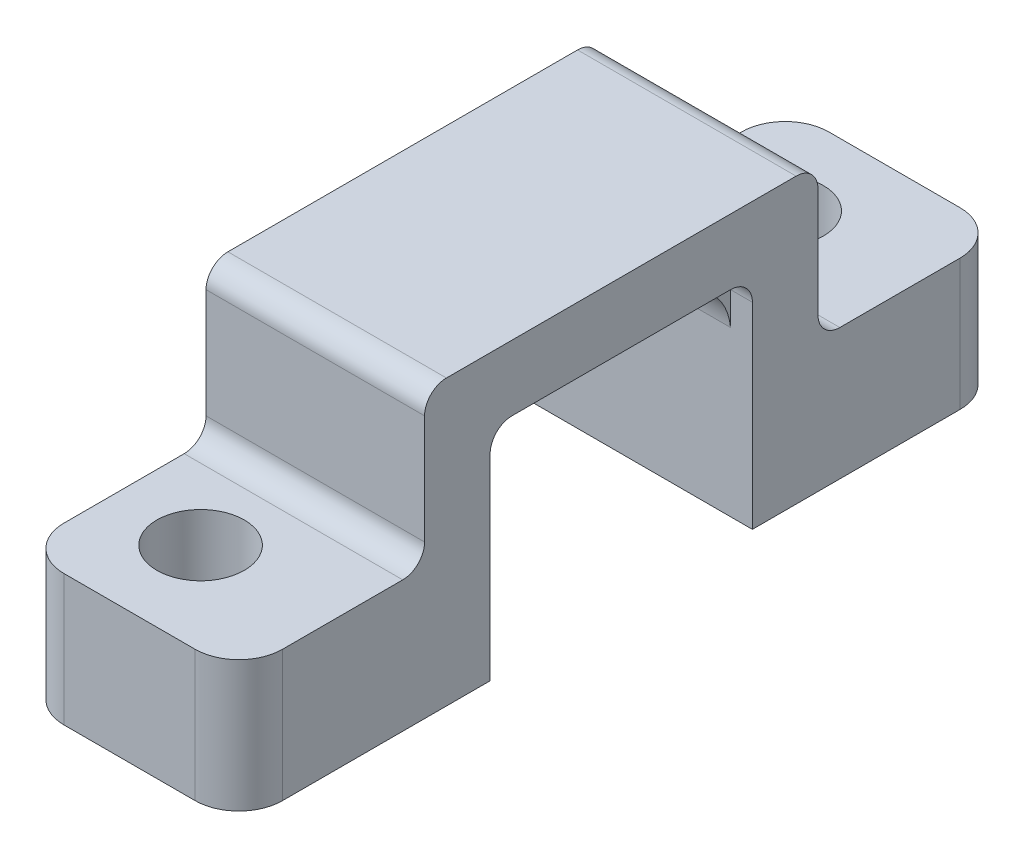
SolidWorks part; units mm, degrees
material "ABS"
ref_plane "Plano frontal" through (0, 0, 0) normal (0, 0, 1) x (1, 0, 0)
ref_plane "Plano superior" through (0, 0, 0) normal (0, 1, 0) x (1, 0, 0)
ref_plane "Plano direito" through (0, 0, 0) normal (1, 0, 0) x (0, 0, -1)
ref_plane "Plano1" through (0, 0, 6) normal (0, 0, -1) x (-1, 0, 0)
sketch "Esboço1" plane through (0, 0, 6) normal (0, 0, -1) x (-1, 0, 0)
  line L0 (-5, 0) -> (13.5, 0)
  line L1 (13.5, 0) -> (13.5, 13)
  line L2 (13.5, 13) -> (-5, 13)
  line L3 (-5, 13) -> (-5, 0)
extrude "Ressalto-extrusão1" add sketch "Esboço1" against normal blind 8
sketch "Esboço2" plane through (0, 0, 14) normal (0, 0, 1) x (1, 0, 0)
  line L0 (-13.5, 3) -> (-5, 3)
  line L1 (-5, 3) -> (-5, 13)
  line L2 (-5, 13) -> (-13.5, 13)
  line L3 (-13.5, 13) -> (-13.5, 3)
extrude "Corte-extrusão1" cut sketch "Esboço2" against normal through all
sketch "Esboço3" plane through (0, 0, 6) normal (0, 0, -1) x (-1, 0, 0)
  line L0 (-5, 10) -> (-5, 13)
  line L1 (-5, 13) -> (5, 13)
  line L2 (5, 13) -> (5, 10)
  line L3 (5, 10) -> (-5, 10)
extrude "Ressalto-extrusão2" add sketch "Esboço3" along normal blind 20
sketch "Esboço4" plane through (0, 10, 0) normal (0, -1, 0) x (1, 0, 0)
  line L0 (-5, -14) -> (-5, -6)
  line L1 (-5, -6) -> (5, -6)
  line L2 (5, -6) -> (5, -14)
  line L3 (5, -14) -> (-5, -14)
extrude "Ressalto-extrusão3" add sketch "Esboço4" along normal blind 10
sketch "Esboço5" plane through (-5, 0, 0) normal (-1, 0, 0) x (0, 0, 1)
  line L0 (-14, 3) -> (-6, 3)
  line L1 (-6, 3) -> (-6, 0)
  line L2 (-6, 0) -> (-14, 0)
  line L3 (-14, 0) -> (-14, 3)
extrude "Ressalto-extrusão4" add sketch "Esboço5" along normal blind 8.5
sketch "Esboço6" plane through (-5, 0, 0) normal (-1, 0, 0) x (0, 0, 1)
  line L0 (-14, 5) -> (-9, 5)
  line L1 (-9, 5) -> (-9, 13)
  line L2 (-9, 13) -> (-14, 13)
  line L3 (-14, 13) -> (-14, 5)
extrude "Corte-extrusão2" cut sketch "Esboço6" against normal through all
sketch "Esboço7" plane through (-5, 0, 0) normal (-1, 0, 0) x (0, 0, 1)
  line L0 (9, 13) -> (9, 5)
  line L1 (9, 5) -> (14, 5)
  line L2 (14, 5) -> (14, 13)
  line L3 (14, 13) -> (9, 13)
extrude "Corte-extrusão3" cut sketch "Esboço7" against normal through all
hole_wizard "Furo de diâmetro Ø4.0 (4)1" positions "Esboço9" profile "Esboço8" hole size "Ø4.0" standard "Ansi Metric"
sketch "Esboço9" plane through (0, 0, 0) normal (0, -1, 0) x (-1, 0, 0)
  point P0 (9.25, 10)
sketch "Esboço8" plane through (-9.25, 0, -10) normal (1, 0, 0) x (0, 0, -1)
  line L0 (0, 0) -> (0, 13)
  line L1 (0, 13) -> (2, 13)
  line L2 (2, 13) -> (2, 0)
  line L5 (2, 0) -> (0, 0)
  line L11 (0, -6.35) -> (0, 107.95) construction
  dimension "Thru Hole Dia." = 4
  dimension "Thru Hole Depth" = 13
hole_wizard "Furo de diâmetro Ø4.0 (4)2" positions "Esboço11" profile "Esboço10" hole size "Ø4.0" standard "Ansi Metric"
sketch "Esboço11" plane through (0, 3, 0) normal (0, 1, 0) x (1, 0, 0)
  point P0 (-9.25, -10)
sketch "Esboço10" plane through (-9.25, 3, 10) normal (1, 0, 0) x (0, 0, 1)
  line L0 (0, 0) -> (0, 3)
  line L1 (0, 3) -> (2, 3)
  line L2 (2, 3) -> (2, 0)
  line L5 (2, 0) -> (0, 0)
  line L11 (0, -6.35) -> (0, 107.95) construction
  dimension "Thru Hole Dia." = 4
  dimension "Thru Hole Depth" = 3
fillet "Filete1" radius 1 6 edges at (0, 10, -6) (0, 5, 9) (0, 13, 9) (0, 5, -9) (0, 10, 6) (0, 13, -9)
fillet "Filete2" radius 2 4 edges at (-13.5, 1.5, -14) (-13.5, 1.5, -6) (-13.5, 1.5, 14) (-13.5, 1.5, 6)
ref_plane "Plano2" through (4, 0, 0) normal (1, 0, 0) x (0, 0, -1)
sketch "Esboço15" plane through (4, 0, 0) normal (1, 0, 0) x (0, 0, -1)
  line L0 (5, 10) -> (-5, 10) construction
  line L1 (-6, 0) -> (6, 0)
  line L2 (-6, 0) -> (-6, 10)
  line L3 (-6, 10) -> (6, 10)
  line L4 (6, 0) -> (6, 10)
  line L5 (6, 0) -> (6, 9) construction
  line L6 (0, 10) -> (0, -49990) construction
  line L8 (6, 0) -> (6, 10)
  arc A0 (-6, 7.5) -> (-3, 10) centre (-3.2324, 7.2289) cw
  arc A1 (6, 7.5) -> (3, 10) centre (3.2324, 7.2289) ccw
  point P14 (0, 10)
  dimension "D3" = 2.7808
  dimension "D1" = 3
  dimension "D2" = 7.5
extrude "Ressalto-extrusão5" add sketch "Esboço15" against normal blind 4 contours L2 A0 L3 | A1 L8 L3
sketch "Esboço16" plane through (0, 3, 0) normal (0, 1, 0) x (1, 0, 0)
  line L1 (-5, -6) -> (-15.5701, -6)
  line L2 (-5, -6) -> (-5, -14.4353)
  line L3 (-5, -14.4353) -> (-15.5701, -14.4353)
  line L4 (-15.5701, -6) -> (-15.5701, -14.4353)
extrude "Corte-extrusão4" cut sketch "Esboço16" against normal blind 10
sketch "Esboço17" plane through (5, 0, 0) normal (1, 0, 0) x (0, 0, -1)
  line L1 (-14, 0) -> (-9, 0)
  line L2 (-14, 0) -> (-14, 6)
  line L3 (-14, 6) -> (-9, 6)
  line L4 (-9, 0) -> (-9, 6)
extrude "Corte-extrusão5" cut sketch "Esboço17" against normal blind 10
sketch "Esboço18" plane through (5, 0, 0) normal (1, 0, 0) x (0, 0, -1)
  line L0 (9, 6) -> (9, 12) construction
  line L1 (14, 0) -> (9, 0)
  line L2 (14, 0) -> (14, 7.1127)
  line L3 (14, 7.1127) -> (9, 7.1127)
  line L4 (9, 0) -> (9, 7.1127)
extrude "Corte-extrusão6" cut sketch "Esboço18" against normal blind 22
sketch "Esboço19" plane through (0, 0, -6) normal (0, 0, 1) x (1, 0, 0)
  line L1 (-5, 3) -> (-13.5, 3)
  line L2 (-5, 3) -> (-5, 0)
  line L3 (-5, 0) -> (-13.5, 0)
  line L4 (-13.5, 3) -> (-13.5, 0)
extrude "Corte-extrusão7" cut sketch "Esboço19" against normal blind 22
sketch "Esboço28" plane through (0, 13, 0) normal (0, 1, 0) x (1, 0, 0)
  line L6 (-5, -9) -> (5, -9)
  line L7 (-5, -9) -> (-5, -15.5)
  line L8 (5, -9) -> (5, -15.5)
  line L9 (3, -17.5) -> (-3, -17.5)
  line L10 (-5, 0) -> (5, 0) construction
  line L11 (-5, 8) -> (-5, -8) construction
  line L12 (5, -8) -> (5, 8) construction
  line L13 (3, 17.5) -> (-3, 17.5)
  line L14 (5, 9) -> (5, 15.5)
  line L15 (-5, 9) -> (-5, 15.5)
  line L16 (-5, 9) -> (5, 9)
  arc A3 (5, -15.5) -> (3, -17.5) centre (3, -15.5) cw
  arc A4 (-5, -15.5) -> (-3, -17.5) centre (-3, -15.5) ccw
  circle A5 centre (-1, -13.25) radius 2
  circle A6 centre (-1, 13.25) radius 2
  arc A7 (-5, 15.5) -> (-3, 17.5) centre (-3, 15.5) cw
  arc A8 (5, 15.5) -> (3, 17.5) centre (3, 15.5) ccw
  dimension "D1" = 2
  dimension "D2" = 4.25
  dimension "D3" = 4
extrude "Ressalto-extrusão9" add sketch "Esboço28" against normal through all
sketch "Esboço29" plane through (-5, 0, 0) normal (-1, 0, 0) x (0, 0, 1)
  line L1 (-17.5, 0) -> (-17.5, 13) construction
  line L3 (-9, 6) -> (-17.5, 6)
  line L4 (-15.5, 0) -> (-6, 0) construction
  line L5 (-9, 6) -> (-9, 13)
  line L6 (-9, 13) -> (-17.5, 13)
  line L7 (-17.5, 13) -> (-17.5, 6)
  line L8 (0, 13) -> (0, 10) construction
  line L9 (-8, 13) -> (8, 13) construction
  line L10 (-5, 10) -> (5, 10) construction
  line L11 (17.5, 13) -> (17.5, 6)
  line L12 (9, 13) -> (17.5, 13)
  line L13 (9, 6) -> (9, 13)
  line L14 (9, 6) -> (17.5, 6)
  dimension "D1" = 6
extrude "Corte-extrusão10" cut sketch "Esboço29" against normal blind 25
fillet "Filete3" radius 1 2 edges at (0, 6, 9) (0, 6, -9)
sketch "Esboço30" plane through (0, 0, 0) normal (0, -1, 0) x (1, 0, 0)
